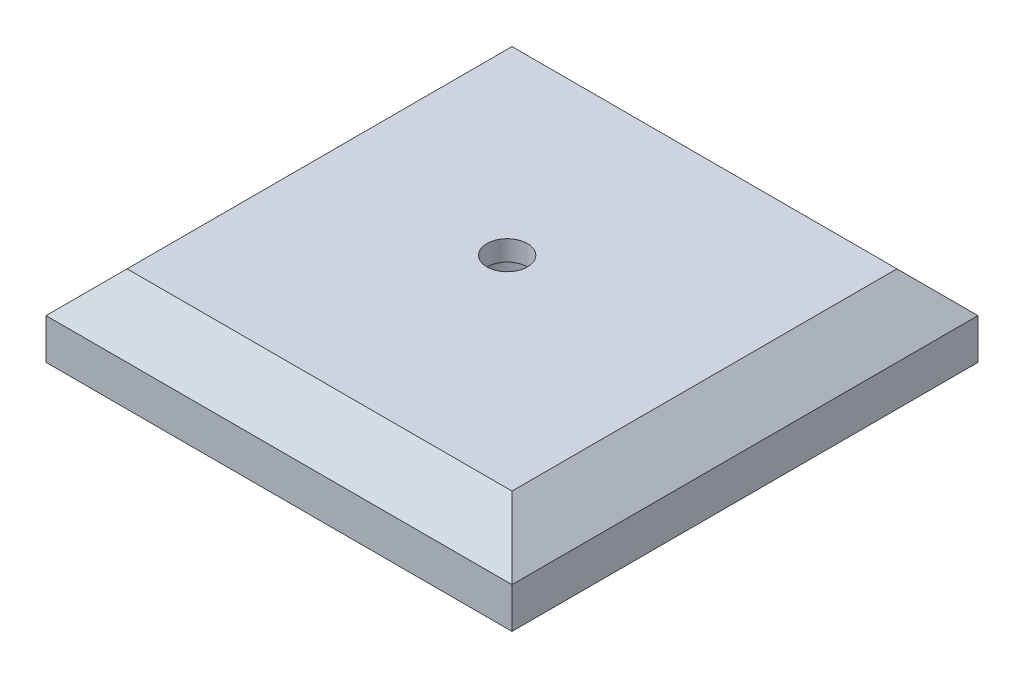
SolidWorks part; units mm, degrees
ref_plane "Front Plane" through (0, 0, 0) normal (0, 0, 1) x (1, 0, 0)
ref_plane "Top Plane" through (0, 0, 0) normal (0, 1, 0) x (1, 0, 0)
ref_plane "Right Plane" through (0, 0, 0) normal (1, 0, 0) x (0, 0, -1)
sketch "Sketch1" plane through (0, 0, 0) normal (0, 1, 0) x (1, 0, 0)
  line L1 (0, 0) -> (-2875, 0)
  line L2 (0, 0) -> (0, -2875)
  line L3 (0, -2875) -> (-2875, -2875)
  line L4 (-2875, 0) -> (-2875, -2875)
  point P5 (0, 0)
extrude "Boss-Extrude1" add sketch "Sketch1" along normal blind 500 contours L2 L1 L4 L3
sketch "Sketch2" plane through (0, 500, 0) normal (0, 1, 0) x (1, 0, 0)
chamfer "Chamfer1" distance 250 distance2 250 4 edges at (-2875, 500, 1437.5) (-1437.5, 500, 0) (0, 500, 1437.5) (-1437.5, 500, 2875)
hole_wizard "Hole2" positions "Sketch5" profile "Sketch6" legacy end condition through all
sketch "Sketch5" plane through (0, 500, 0) normal (0, 1, 0) x (1, 0, 0)
  point P0 (-1524.9552, -1379.8128)
  point P3 (-1524.9552, -1379.8128)
sketch "Sketch6" plane through (-1524.9552, 500, 1379.8128) normal (1, 0, 0) x (0, 0, 1)
  line L0 (0, 0) -> (0, 500)
  line L1 (0, 500) -> (250, 500)
  line L3 (250, 500) -> (250, 125)
  line L4 (250, 125) -> (125, 125)
  line L5 (125, 125) -> (125, 0)
  line L7 (125, 0) -> (0, 0)
  line L11 (0, -6.35) -> (0, 107.95) construction
  dimension "Thru Hole Dia." = 500
  dimension "Thru Hole Depth" = 500
  dimension "C'Bore Dia." = 250
  dimension "C'Bore Depth" = 125
